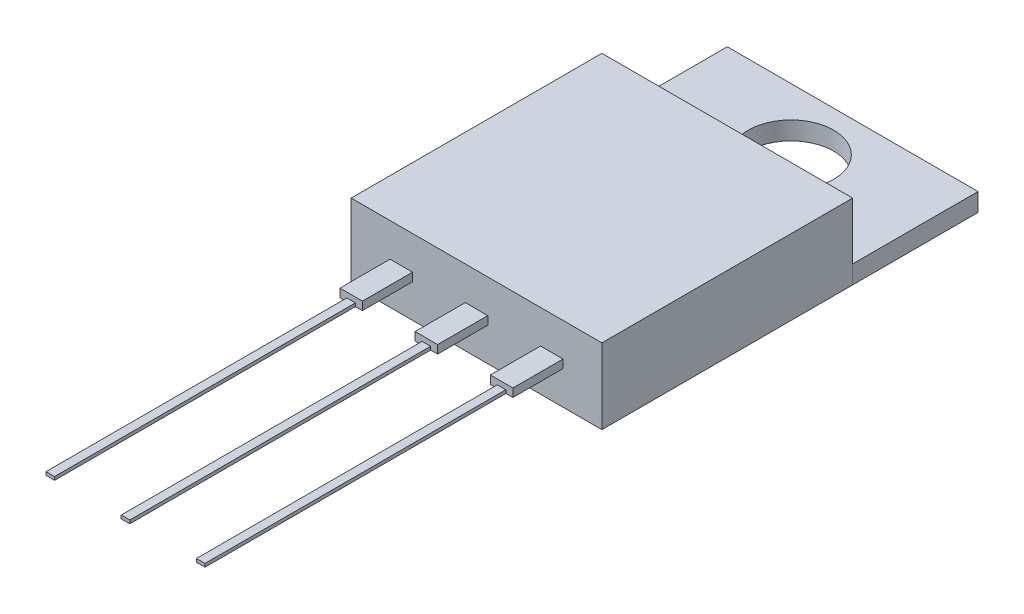
SolidWorks part; units mm, degrees
ref_plane "Front Plane" through (0, 0, 0) normal (0, 0, 1) x (1, 0, 0)
ref_plane "Top Plane" through (0, 0, 0) normal (0, 1, 0) x (1, 0, 0)
ref_plane "Right Plane" through (0, 0, 0) normal (1, 0, 0) x (0, 0, -1)
other "Center of Mass"
sketch "Sketch1" plane through (0, 0, 0) normal (0, 1, 0) x (1, 0, 0)
  line L1 (-5, -5) -> (5, -5)
  line L2 (-5, -5) -> (-5, 5)
  line L3 (-5, 5) -> (5, 5)
  line L4 (5, -5) -> (5, 5)
  line L5 (-5, -5) -> (5, 5) construction
  line L6 (-5, 5) -> (5, -5) construction
  point P0 (0, 0)
  dimension "D1" = 10
  dimension "D2" = 10
extrude "Boss-Extrude1" add sketch "Sketch1" along normal blind 3
sketch "Sketch2" plane through (0, 0, -5) normal (0, 0, -1) x (-1, 0, 0)
  line L0 (-5, 3) -> (-5, 0) construction
  line L1 (-5, 0.7258) -> (5, 0.7258)
  line L2 (-5, 0.7258) -> (-5, 0)
  line L3 (-5, 0) -> (5, 0)
  line L4 (5, 0.7258) -> (5, 0)
extrude "Boss-Extrude2" add sketch "Sketch2" along normal blind 5 separate body
sketch "Sketch3" plane through (0, 0, 5) normal (0, 0, 1) x (1, 0, 0)
  line L0 (2.5515, 1.6655) -> (3.4485, 1.6655)
  line L1 (-0.4485, 1.3345) -> (0.4485, 1.3345)
  line L2 (-0.4485, 1.3345) -> (-0.4485, 1.6655)
  line L3 (-0.4485, 1.6655) -> (0.4485, 1.6655)
  line L4 (0.4485, 1.3345) -> (0.4485, 1.6655)
  line L5 (-0.4485, 1.3345) -> (0.4485, 1.6655) construction
  line L6 (-0.4485, 1.6655) -> (0.4485, 1.3345) construction
  line L7 (3.4485, 1.3345) -> (3.4485, 1.6655)
  line L8 (2.5515, 1.3345) -> (3.4485, 1.3345)
  line L9 (2.5515, 1.3345) -> (2.5515, 1.6655)
  line L10 (-3.4485, 1.6655) -> (-2.5515, 1.6655)
  line L11 (-3.4485, 1.3345) -> (-3.4485, 1.6655)
  line L12 (-3.4485, 1.3345) -> (-2.5515, 1.3345)
  line L13 (-2.5515, 1.3345) -> (-2.5515, 1.6655)
  point P0 (0, 1.5)
  dimension "D1" = 2
  dimension "D2" = 2
extrude "Boss-Extrude3" add sketch "Sketch3" along normal blind 2 separate body
sketch "Sketch4" plane through (0, 0, 7) normal (0, 0, 1) x (1, 0, 0)
  line L0 (-3.4485, 1.3345) -> (-2.5515, 1.3345) construction
  line L1 (-3.1705, 1.4656) -> (-2.8295, 1.4656)
  line L2 (-3.1705, 1.4656) -> (-3.1705, 1.3345)
  line L3 (-3.1705, 1.3345) -> (-2.8295, 1.3345)
  line L4 (-2.8295, 1.4656) -> (-2.8295, 1.3345)
  line L5 (-3.1705, 1.4656) -> (-2.8295, 1.3345) construction
  line L6 (-3.1705, 1.3345) -> (-2.8295, 1.4656) construction
  line L7 (-0.1705, 1.4656) -> (0.1705, 1.3345) construction
  line L8 (-0.1705, 1.3345) -> (0.1705, 1.4656) construction
  line L9 (-0.1705, 1.4656) -> (-0.1705, 1.3345)
  line L10 (-0.1705, 1.4656) -> (0.1705, 1.4656)
  line L11 (0.1705, 1.4656) -> (0.1705, 1.3345)
  line L12 (-0.1705, 1.3345) -> (0.1705, 1.3345)
  line L13 (2.8295, 1.4656) -> (3.1705, 1.3345) construction
  line L14 (2.8295, 1.3345) -> (3.1705, 1.4656) construction
  line L15 (2.8295, 1.4656) -> (2.8295, 1.3345)
  line L16 (2.8295, 1.4656) -> (3.1705, 1.4656)
  line L17 (3.1705, 1.4656) -> (3.1705, 1.3345)
  line L18 (2.8295, 1.3345) -> (3.1705, 1.3345)
  point P0 (-3, 1.4001)
  point P9 (0, 1.4001)
  point P14 (3, 1.4001)
  dimension "D1" = 3
extrude "Boss-Extrude4" add sketch "Sketch4" along normal blind 12 separate body
sketch "Sketch5" plane through (0, 0.7258, 0) normal (0, 1, 0) x (1, 0, 0)
  circle A0 centre (0, 7.5404) radius 1.7028
extrude "Cut-Extrude1" cut sketch "Sketch5" against normal blind 12
